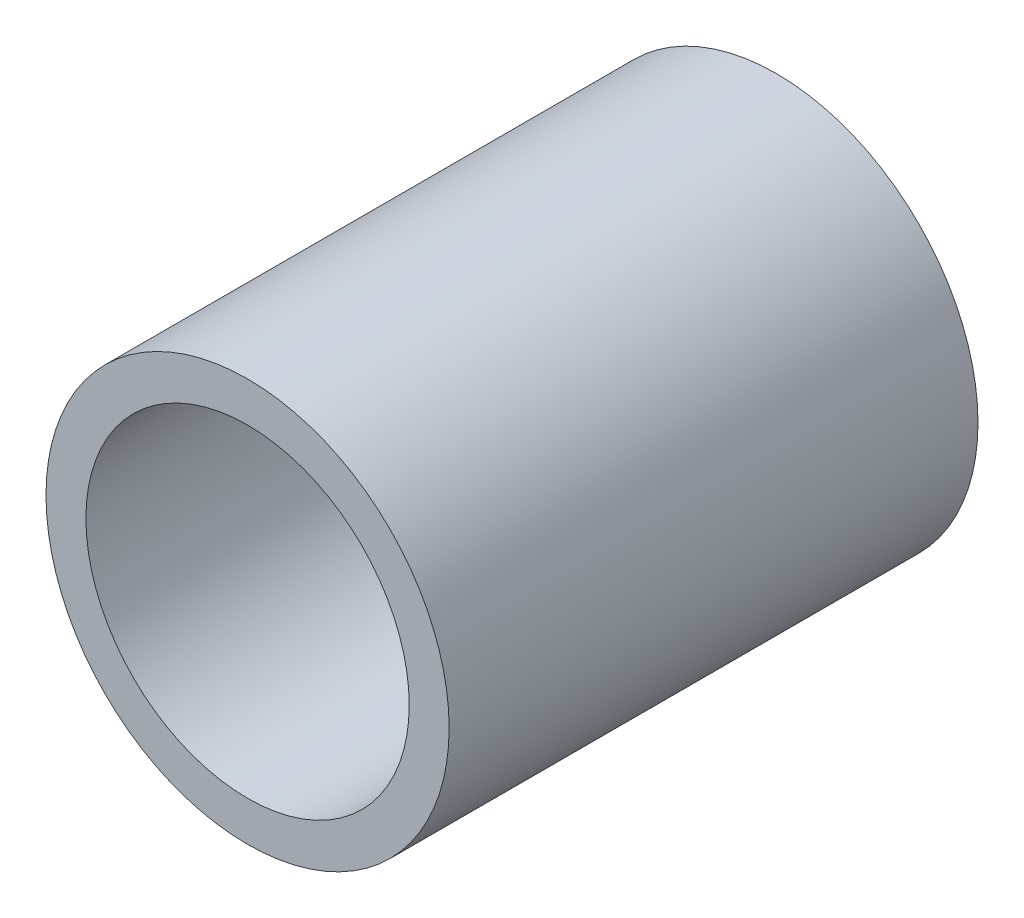
SolidWorks part; units mm, degrees
ref_plane "Front Plane" through (0, 0, 0) normal (0, 0, 1) x (1, 0, 0)
ref_plane "Top Plane" through (0, 0, 0) normal (0, 1, 0) x (1, 0, 0)
ref_plane "Right Plane" through (0, 0, 0) normal (1, 0, 0) x (0, 0, -1)
sketch "Sketch1" plane through (0, 0, 0) normal (0, 0, 1) x (1, 0, 0)
  circle A0 centre (0, 0) radius 4.05
  dimension "D1" = 8.1
extrude "Extrude-Thin1" add sketch "Sketch1" along normal blind 13.25 thin
